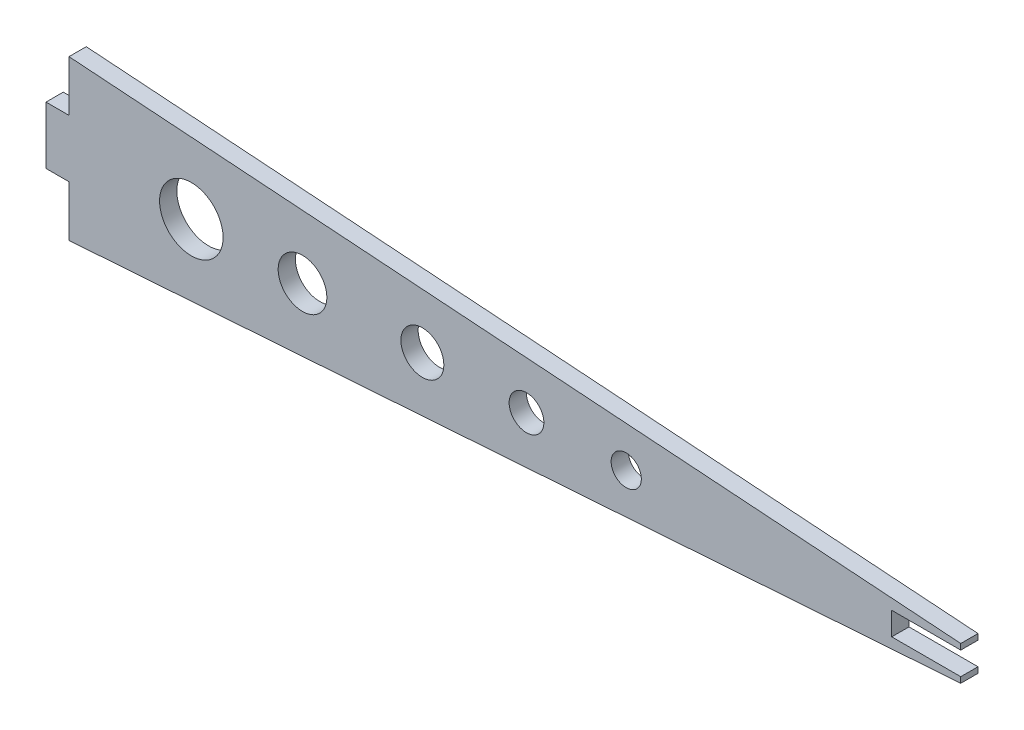
SolidWorks part; units mm, degrees
ref_plane "前视基准面" through (0, 0, 0) normal (0, 0, 1) x (1, 0, 0)
ref_plane "上视基准面" through (0, 0, 0) normal (0, 1, 0) x (1, 0, 0)
ref_plane "右视基准面" through (0, 0, 0) normal (1, 0, 0) x (0, 0, -1)
sketch "Model" plane through (0, 0, 0) normal (0, 0, 1) x (1, 0, 0)
  line L0 (244.0594, -194.2526) -> (166.5269, -199.6742)
  line L1 (166.5269, -185.831) -> (166.5269, -190.2526)
  line L2 (166.5269, -195.2526) -> (164.5269, -195.2526)
  line L3 (164.5269, -195.2526) -> (164.5269, -190.2526)
  line L4 (164.5269, -190.2526) -> (166.5269, -190.2526)
  line L5 (166.5269, -195.2526) -> (166.5269, -199.6742)
  line L6 (166.5269, -185.831) -> (244.0594, -191.2526)
  line L7 (244.0594, -191.2526) -> (244.0594, -191.7526)
  line L8 (238.0594, -192.7526) -> (238.0594, -191.7526)
  line L9 (238.0594, -192.7526) -> (238.0594, -193.7526)
  line L10 (244.0594, -191.7526) -> (238.0594, -191.7526)
  line L11 (244.0594, -193.7526) -> (238.0594, -193.7526)
  line L12 (244.0594, -193.7526) -> (244.0594, -194.2526)
  circle A0 centre (177.163, -192.7526) radius 2.7616
  circle A1 centre (197.2501, -192.7526) radius 1.8666
  circle A2 centre (214.9741, -192.7526) radius 1.3132
  circle A3 centre (186.8291, -192.7526) radius 2.1167
  circle A4 centre (206.303, -192.7526) radius 1.5097
extrude "凸台-拉伸1" add sketch "Model" along normal blind 1.5
